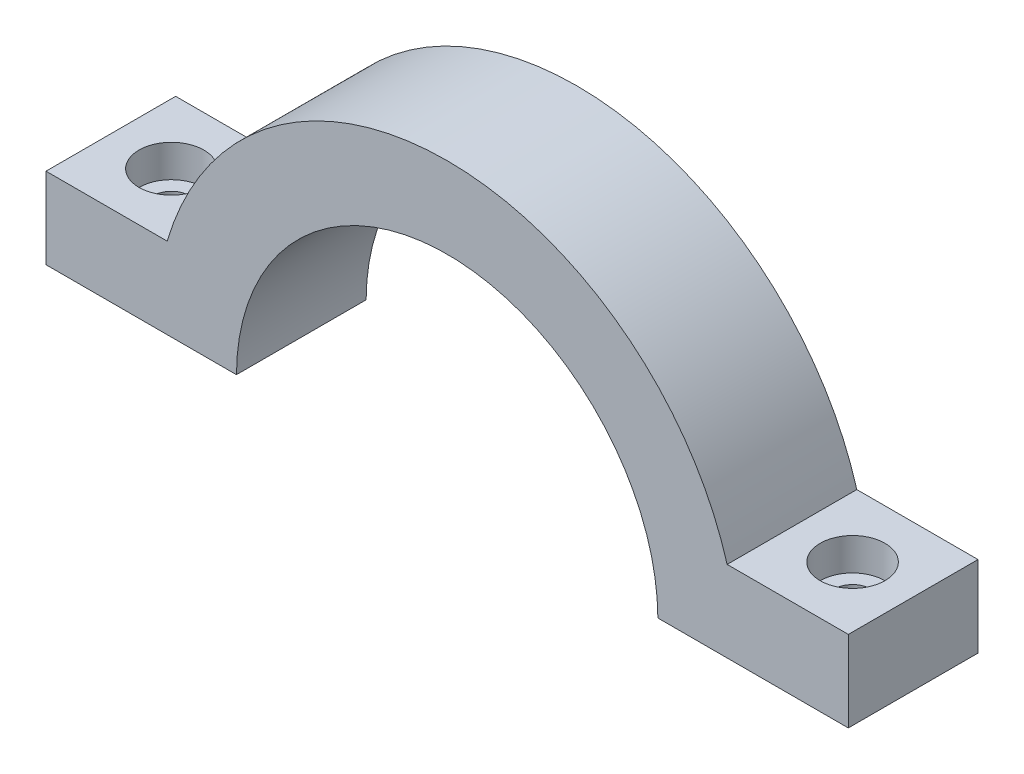
SolidWorks part; units mm, degrees
ref_plane "Front Plane" through (0, 0, 0) normal (0, 0, 1) x (1, 0, 0)
ref_plane "Top Plane" through (0, 0, 0) normal (0, 1, 0) x (1, 0, 0)
ref_plane "Right Plane" through (0, 0, 0) normal (1, 0, 0) x (0, 0, -1)
sketch "Sketch2" plane through (0, 0, 0) normal (0, 0, 1) x (1, 0, 0)
  line L0 (-47.3556, 0) -> (47.3556, 0) construction
  line L1 (-49.5, 0.125) -> (-25.9997, 0.125)
  line L2 (25.9997, 0.125) -> (49.5, 0.125)
  line L3 (-49.5, 0.125) -> (-49.5, 10.125)
  line L4 (-49.5, 10.125) -> (-34.5468, 10.125)
  line L5 (49.5, 0.125) -> (49.5, 10.125)
  line L6 (49.5, 10.125) -> (34.5468, 10.125)
  arc A0 (25.9997, 0.125) -> (-25.9997, 0.125) centre (0, 0) ccw
  arc A2 (34.5468, 10.125) -> (-34.5468, 10.125) centre (0, 0) ccw
  dimension "D1" = 52
  dimension "D2" = 10
  dimension "D3" = 99
  dimension "D4" = 10
  dimension "D5" = 0.25
extrude "Boss-Extrude1" add sketch "Sketch2" against normal blind 16
sketch "Sketch3" plane through (0, 10.125, 0) normal (0, 1, 0) x (1, 0, 0)
  line L0 (-49.5, 8) -> (49.5, 8) construction
  line L1 (-49.5, 16) -> (-49.5, 0) construction
  line L2 (49.5, 16) -> (49.5, 0) construction
  line L3 (-42.0234, 16) -> (-42.0234, 0) construction
  line L4 (-34.5468, 16) -> (-49.5, 16) construction
  line L5 (-34.5468, 0) -> (-49.5, 0) construction
  line L6 (42.0234, 16) -> (42.0234, 0) construction
  line L7 (49.5, 16) -> (34.5468, 16) construction
  line L8 (49.5, 0) -> (34.5468, 0) construction
  point P18 (-42.0234, 8)
  point P19 (42.0234, 8)
sketch "Sketch4" plane through (0, 10.125, 0) normal (0, 1, 0) x (1, 0, 0)
  line L0 (-42.0234, 16) -> (-42.0234, 0) construction
  line L1 (42.0234, 16) -> (42.0234, 0) construction
  point P0 (-42.0234, 8)
  point P4 (42.0234, 8)
hole_wizard "CBORE for M4 SHCS1" positions "Sketch4" profile "Sketch5" counterbore size "M4" standard "ANSI Metric" end condition through all
sketch "Sketch5" plane through (-42.0234, 10.125, -8) normal (1, 0, 0) x (0, 0, 1)
  line L0 (0, 0) -> (0, 10)
  line L1 (0, 10) -> (2.25, 10)
  line L3 (2.25, 10) -> (2.25, 4)
  line L4 (2.25, 4) -> (4, 4)
  line L5 (4, 4) -> (4, 0)
  line L7 (4, 0) -> (0, 0)
  line L11 (0, -6.35) -> (0, 107.95) construction
  dimension "Thru Hole Dia." = 4.5
  dimension "Thru Hole Depth" = 10
  dimension "C'Bore Dia." = 8
  dimension "C'Bore Depth" = 4
